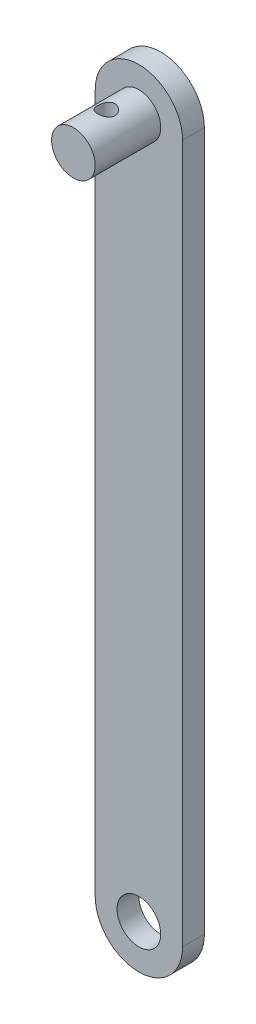
SolidWorks part; units mm, degrees
ref_plane "Front Plane" through (0, 0, 0) normal (0, 0, 1) x (1, 0, 0)
ref_plane "Top Plane" through (0, 0, 0) normal (0, 1, 0) x (1, 0, 0)
ref_plane "Right Plane" through (0, 0, 0) normal (1, 0, 0) x (0, 0, -1)
sketch "Sketch1" plane through (0, 0, 0) normal (0, 0, 1) x (1, 0, 0)
  line L0 (-12.7, -101.6) -> (-12.7, 101.6)
  line L1 (12.7, -101.6) -> (12.7, 101.6)
  line L2 (-22.7949, 0) -> (48.0321, 0) construction
  line L3 (-65.5814, 114.3) -> (65.5814, 114.3) construction
  arc A0 (-12.7, 101.6) -> (12.7, 101.6) centre (0, 101.6) cw
  circle A1 centre (0, 101.6) radius 6.35
  circle A2 centre (0, -101.6) radius 6.35
  arc A3 (-12.7, -101.6) -> (12.7, -101.6) centre (0, -101.6) ccw
  point P2 (-12.7, 0)
  point P13 (12.7, 0)
  point P15 (0, 114.3)
  dimension "D1" = 12.7
  dimension "D3" = 12.7
  dimension "D2" = 101.6
  dimension "D4" = 12.7
extrude "Boss-Extrude1" add sketch "Sketch1" along normal blind 6.35
sketch "Sketch2" plane through (0, 0, 0) normal (0, 0, 1) x (1, 0, 0)
  circle A0 centre (0, 101.6) radius 6.35
extrude "Boss-Extrude3" add sketch "Sketch2" along normal blind 25.4
sketch "Sketch4" plane through (0, 0, 0) normal (0, 0, 1) x (1, 0, 0)
  circle A0 centre (0, -101.6) radius 6.35
  dimension "D1" = 12.7
sketch "Sketch5" plane through (0, 0, 0) normal (0, 1, 0) x (1, 0, 0)
  line L0 (0, -6.35) -> (0, -25.4) construction
  line L1 (-12.7, -6.35) -> (12.7, -6.35) construction
  line L2 (-6.35, -25.4) -> (6.35, -25.4) construction
  circle A0 centre (0, -15.875) radius 2.54
  point P2 (0, -15.875)
  dimension "D1" = 5.08
extrude "Cut-Extrude2" cut sketch "Sketch5" along normal through all
